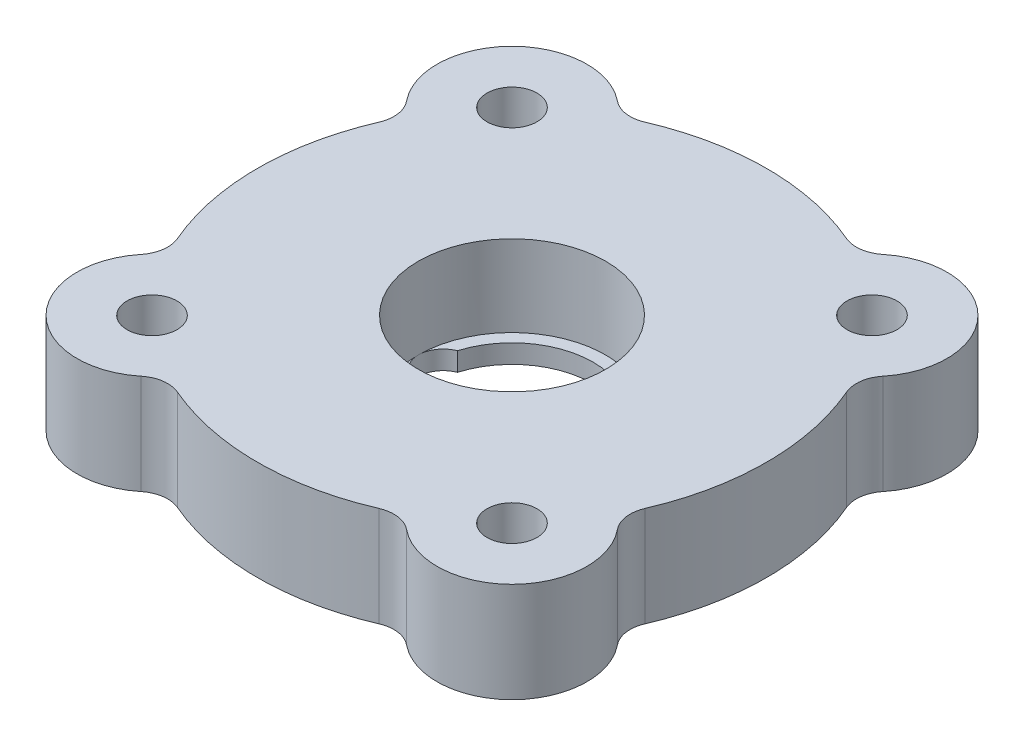
SolidWorks part; units mm, degrees
material "1060 Alloy"
ref_plane "Front" through (0, 0, 0) normal (0, 0, 1) x (1, 0, 0)
ref_plane "Top" through (0, 0, 0) normal (0, 1, 0) x (1, 0, 0)
ref_plane "Right" through (0, 0, 0) normal (1, 0, 0) x (0, 0, -1)
sketch "Sketch1" plane through (0, 0, 0) normal (0, 1, 0) x (1, 0, 0)
  line L0 (0, 0) -> (0, 40.75) construction
  circle A0 centre (-28.8146, 28.8146) radius 4
  circle A1 centre (28.8146, 28.8146) radius 4
  circle A2 centre (28.8146, -28.8146) radius 4
  circle A3 centre (-28.8146, -28.8146) radius 4
  circle A4 centre (0, 0) radius 13
  arc A5 (-21.2538, 38.1331) -> (-38.1331, 21.2538) centre (-28.8146, 28.8146) ccw
  arc A6 (38.1331, 21.2538) -> (21.2538, 38.1331) centre (28.8146, 28.8146) ccw
  arc A7 (21.2538, -38.1331) -> (38.1331, -21.2538) centre (28.8146, -28.8146) ccw
  arc A8 (-38.1331, -21.2538) -> (-21.2538, -38.1331) centre (-28.8146, -28.8146) ccw
  arc A9 (-37.4239, 16.1249) -> (-37.4239, -16.1249) centre (0, 0) ccw
  arc A10 (-16.1249, -37.4239) -> (16.1249, -37.4239) centre (0, 0) ccw
  arc A11 (37.4239, -16.1249) -> (37.4239, 16.1249) centre (0, 0) ccw
  arc A12 (-16.1249, 37.4239) -> (-21.2538, 38.1331) centre (-18.1035, 42.0158) cw
  arc A13 (16.1249, 37.4239) -> (-16.1249, 37.4239) centre (0, 0) ccw
  arc A14 (21.2538, 38.1331) -> (16.1249, 37.4239) centre (18.1035, 42.0158) cw
  arc A15 (38.1331, 21.2538) -> (37.4239, 16.1249) centre (42.0158, 18.1035) ccw
  arc A16 (37.4239, -16.1249) -> (38.1331, -21.2538) centre (42.0158, -18.1035) ccw
  arc A17 (21.2538, -38.1331) -> (16.1249, -37.4239) centre (18.1035, -42.0158) ccw
  arc A18 (-16.1249, -37.4239) -> (-21.2538, -38.1331) centre (-18.1035, -42.0158) ccw
  arc A19 (-37.4239, -16.1249) -> (-38.1331, -21.2538) centre (-42.0158, -18.1035) cw
  arc A20 (-37.4239, 16.1249) -> (-38.1331, 21.2538) centre (-42.0158, 18.1035) ccw
  point P0 (0, 0)
  point P17 (0, 0)
  point P27 (0, 0)
  dimension "D5" = 8
  dimension "D6" = 26
  dimension "D1" = 5
  dimension "D2" = 12
  dimension "D3" = 40.75
  dimension "D4" = 4
  dimension "D8" = 4
extrude "body and main holes" add sketch "Sketch1" along normal blind 16
sketch "Sketch3" plane through (0, 16, 0) normal (0, -1, 0) x (1, 0, 0)
  circle A0 centre (0, 0) radius 15
  dimension "D1" = 30
extrude "bearing hole" cut sketch "Sketch3" along normal blind 13
sketch "section plane alignment 1" plane through (0, 16, 0) normal (0, 1, 0) x (1, 0, 0)
  line L0 (-28.8146, 28.8146) -> (28.8146, -28.8146) construction
sketch "section plane alignment 2" plane through (0, 0, 0) normal (0, -1, 0) x (1, 0, 0)
  line L0 (-28.8146, -28.8146) -> (28.8146, 28.8146) construction
sketch "Sketch4" plane through (0, 0, 0) normal (0, -1, 0) x (1, 0, 0)
  line L1 (11, 4) -> (-11, 4)
  line L2 (11, 4) -> (11, -4) construction
  line L3 (11, -4) -> (-11, -4)
  line L4 (-11, 4) -> (-11, -4) construction
  line L5 (11, 4) -> (-11, -4) construction
  line L6 (11, -4) -> (-11, 4) construction
  arc A0 (-11, 4) -> (-11, -4) centre (-11, 0) ccw
  arc A1 (11, -4) -> (11, 4) centre (11, 0) ccw
  circle A3 centre (0, 0) radius 15 construction
  point P0 (0, 0)
  dimension "D1" = 8
extrude "bearing removal slot" cut sketch "Sketch4" against normal blind 3
equation "\"D3@Sketch1\"=\"square plate bolt pattern diameter\"/2"
equation "\"D1@body and main holes\"=\"bearing plate thickness\""
equation "\"D1@Sketch3\" = \"bearing OD\""
equation "\"D1@bearing hole\"=\"bearing plate thickness\" - \"bearing plate stop depth\""
equation "\"D5@Sketch1\" = \"square plate bolt bore\""
equation "\"D6@Sketch1\" = \"bearing plate stop ID\""
equation "\"bearing inner race thickness\"= 1mm"
equation "\"bearing bore\"= \"bearing depth\" + 1mm"
equation "\"square plate bolt pattern diameter\"= \"motor OD\" + \"square plate bolt head diameter\" + 4mm"
equation "\"bearing plate thickness\"= \"bearing bore\" + \"bearing plate stop depth\" + \"shaft bearing stop length\""
equation "\"bearing plate stop ID\"= \"bearing OD\" - 4mm"
equation "\"bearing plate stop depth\"= 3mm"
equation "\"square plate bolt bore\"= 8mm"
equation "\"square plate bolt head diameter\"= 13.5mm"
equation "\"motor OD\"= 64mm"
equation "\"bearing OD\"= 30mm"
equation "\"bearing depth\"= 9mm"
equation "\"motor mount post radius\"= ( 3 * \"square plate bolt bore\" ) / 2"
equation "\"D2@Sketch1\"=\"motor mount post radius\""
equation "\"D1@bearing removal slot\" = \"bearing plate stop depth\""
equation "\"bearing ID\"= 10mm"
equation "\"bearing outer race thickness\"= 1mm"
equation "\"small seal OD\"= 20mm"
equation "\"small seal ID\"= 8mm"
equation "\"small seal depth\"= 8.3mm"
equation "\"small seal bore\"= \"small seal depth\" + 1mm"
equation "\"big seal OD\"= 27mm"
equation "\"big seal ID\"= 15mm"
equation "\"big seal depth\"= 8.3mm"
equation "\"big seal bore\"= \"big seal depth\" + 1mm"
equation "\"coupler motor shaft hole ID\"= 8mm"
equation "\"coupler OD\"= 17mm"
equation "\"coupler length\"= 25mm"
equation "\"motor shaft diameter\"= 8mm"
equation "\"motor shaft pride\"= 32mm"
equation "\"motor to bearing plate distance\"= \"motor shaft pride\" + 2mm +\"coupler length\"/2"
equation "\"motor mount center bore\"= \"coupler OD\"+ 4mm"
equation "\"motor mount m4 screw hole diameter\"= 4mm"
equation "\"small seal plate lip depth\"= 2mm"
equation "\"shaft bearing section length\"= \"bearing plate stop depth\" + \"bearing depth\""
equation "\"shaft bearing stop diameter\"= \"bearing ID\" + 4mm"
equation "\"shaft bearing stop length\"= 3mm"
